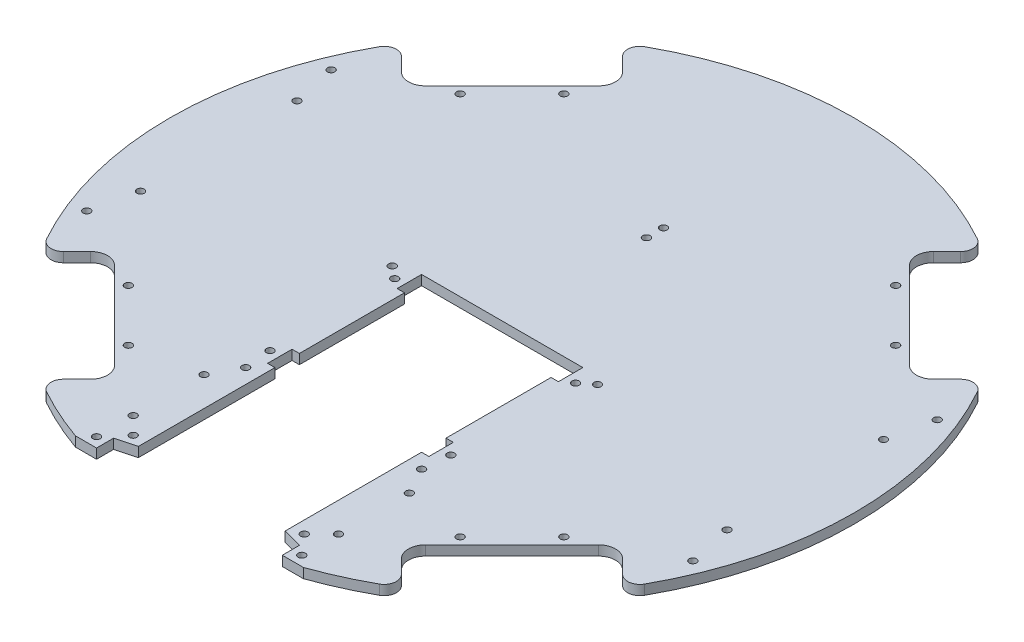
SolidWorks part; units mm, degrees
material "1060 Alloy"
ref_plane "Front Plane" through (0, 0, 0) normal (0, 0, 1) x (1, 0, 0)
ref_plane "Top Plane" through (0, 0, 0) normal (0, 1, 0) x (1, 0, 0)
ref_plane "Right Plane" through (0, 0, 0) normal (1, 0, 0) x (0, 0, -1)
sketch "Sketch1" plane through (0, 0, 0) normal (0, 1, 0) x (1, 0, 0)
  circle A0 centre (0, 0) radius 140
  dimension "D1" = 280
extrude "Boss-Extrude1" add sketch "Sketch1" along normal blind 4
sketch "Sketch7" plane through (0, 4, 0) normal (0, 1, 0) x (1, 0, 0)
  line L0 (-99.0303, -63.6043) -> (-63.6043, -99.0303)
  line L1 (-108.8591, -63.6043) -> (-121.6224, -76.3675)
  line L2 (-63.6043, -108.8591) -> (-76.3675, -121.6224)
  line L3 (-121.6224, -76.3675) -> (-76.3675, -121.6224)
  line L4 (0, 0) -> (-98.9949, -98.9949) construction
  line L7 (0, 0) -> (0, 130) construction
  circle A0 centre (0, 0) radius 140 construction
  arc A1 (-108.8591, -63.6043) -> (-99.0303, -63.6043) centre (-103.9447, -68.5186) cw
  arc A2 (-63.6043, -99.0303) -> (-63.6043, -108.8591) centre (-68.5186, -103.9447) cw
  dimension "D4" = 6.95
  dimension "D1" = 115
  dimension "D2" = 64
  dimension "D3" = 135
extrude "Cut-Extrude4" cut sketch "Sketch7" against normal up to next
sketch "Sketch9" plane through (0, 4, 0) normal (0, 1, 0) x (1, 0, 0)
  line L1 (-63.6043, -99.0303) -> (-99.0303, -63.6043) construction
  line L4 (-108.8591, -63.6043) -> (-119.0017, -73.7469) construction
  circle A0 centre (-89.0955, -67.8823) radius 1.5
  circle A1 centre (-67.8823, -89.0955) radius 1.5
  dimension "D4" = 3
  dimension "D1" = 4
  dimension "D2" = 30
  dimension "D3" = 17
  dimension "D5" = 4
extrude "Cut-Extrude6" cut sketch "Sketch9" against normal up to next
fillet "Fillet1" radius 5 2 edges at (-73.7469, 2, 119.0017) (-119.0017, 2, 73.7469)
pattern_circular "CirPattern1" count 4 over 360 about axis through (0, 0, 0) along (0, 1, 0) of "Cut-Extrude4", "Fillet1", "Cut-Extrude6"
sketch "Sketch2" plane through (0, 4, 0) normal (0, 1, 0) x (1, 0, 0)
  line L0 (-46.6476, -132) -> (-38, -132)
  line L1 (-30, -122.8564) -> (-30, -67)
  line L2 (-33, -4) -> (33, -4)
  line L3 (30, -67) -> (30, -122.8564)
  line L4 (38, -132) -> (46.6476, -132)
  line L5 (46.6476, -132) -> (46.6476, -140)
  line L6 (46.6476, -140) -> (-46.6476, -140)
  line L7 (-46.6476, -140) -> (-46.6476, -132)
  line L8 (-33, -57) -> (-33, -67)
  line L9 (-33, -67) -> (-30, -67)
  line L10 (33, -57) -> (33, -67)
  line L11 (33, -67) -> (30, -67)
  line L12 (-33, -57) -> (-30, -57)
  line L13 (-30, -57) -> (-30, -14)
  line L14 (-30, -14) -> (-33, -14)
  line L15 (-33, -14) -> (-33, -4)
  line L16 (33, -4) -> (33, -14)
  line L17 (33, -14) -> (30, -14)
  line L18 (30, -14) -> (30, -57)
  line L19 (30, -57) -> (33, -57)
  line L20 (-38, -132) -> (-38, -125)
  line L21 (-38, -125) -> (-30, -122.8564)
  line L22 (38, -132) -> (38, -125)
  line L23 (38, -125) -> (30, -122.8564)
  circle A0 centre (0, 0) radius 140 construction
  dimension "D8" = 3
  dimension "D5" = 63
  dimension "D6" = 66
  dimension "D1" = 8
  dimension "D2" = 65
  dimension "D3" = 60
  dimension "D4" = 16.6476
  dimension "D7" = 10
  dimension "D9" = 76
  dimension "D10" = 7
  dimension "D11" = 105
extrude "Cut-Extrude1" cut sketch "Sketch2" against normal up to next
fillet "Fillet3" radius 1.5 8 edges at (67.8823, 0, 90.5955) (89.0955, 0, 69.3823) (89.0955, 0, -66.3823) (67.8823, 0, -87.5955) (-67.8823, 0, -87.5955) (-89.0955, 0, -66.3823) (-67.8823, 0, 90.5955) (-89.0955, 0, 69.3823)
sketch "Sketch10" plane through (0, 4, 0) normal (0, 1, 0) x (1, 0, 0)
  line L0 (-33, -57) -> (-33, -67) construction
  line L1 (33, -67) -> (33, -57) construction
  line L2 (-33, -67) -> (-30, -67) construction
  line L4 (-30, -14) -> (-33, -14) construction
  line L5 (33, -4) -> (-33, -4) construction
  circle A0 centre (-37, -62) radius 1.5
  circle A1 centre (37, -62) radius 1.5
  circle A2 centre (-37, -11) radius 1.5
  circle A3 centre (37, -11) radius 1.5
  circle A4 centre (-42, -7) radius 1.5
  circle A5 centre (42, -7) radius 1.5
  point P17 (-31.5, -14)
  dimension "D3" = 3
  dimension "D1" = 4
  dimension "D2" = 4
  dimension "D4" = 5
  dimension "D5" = 3
  dimension "D6" = 3
  dimension "D7" = 5
  dimension "D8" = 5
extrude "Cut-Extrude7" cut sketch "Sketch10" against normal up to next
sketch "Sketch13" plane through (0, 4, 0) normal (0, 1, 0) x (1, 0, 0)
  line L0 (-38, -132) -> (-46.6476, -132) construction
  line L1 (-38, -132) -> (-46.6476, -132) construction
  circle A0 centre (-42, -84) radius 1.5
  circle A1 centre (-42, -113) radius 1.5
  circle A2 centre (42, -113) radius 1.5
  circle A3 centre (42, -84) radius 1.5
  dimension "D1" = 3
  dimension "D2" = 19
  dimension "D3" = 48
  dimension "D4" = 42
  dimension "D5" = 42
extrude "Cut-Extrude9" cut sketch "Sketch13" against normal up to next
sketch "Sketch16" plane through (0, 4, 0) normal (0, 1, 0) x (1, 0, 0)
  circle A0 centre (0, 62) radius 1.5
  circle A4 centre (0, 55) radius 1.5
  dimension "D2" = 3
  dimension "D5" = 3
  dimension "D1" = 62
  dimension "D7" = 55
extrude "Cut-Extrude12" cut sketch "Sketch16" against normal up to next
sketch "Sketch17" plane through (0, 4, 0) normal (0, 1, 0) x (1, 0, 0)
  circle A0 centre (-124, 50) radius 1.5
  circle A1 centre (-124, -50) radius 1.5
  circle A2 centre (124, 50) radius 1.5
  circle A3 centre (124, -50) radius 1.5
  dimension "D1" = 3
  dimension "D2" = 50
  dimension "D3" = 50
  dimension "D4" = 124
  dimension "D5" = 124
extrude "Cut-Extrude13" cut sketch "Sketch17" against normal up to next
sketch "Sketch18" plane through (0, 4, 0) normal (0, 1, 0) x (1, 0, 0)
  line L1 (-27, -4) -> (27, -4)
  line L2 (-27, -4) -> (-27, 46)
  line L3 (-27, 46) -> (27, 46)
  line L4 (27, -4) -> (27, 46)
  line L5 (33, -4) -> (-33, -4) construction
  dimension "D1" = 50
  dimension "D2" = 54
  dimension "D3" = 27
extrude "Cut-Extrude14" [suppressed] cut sketch "Sketch18" against normal blind 0.8
sketch "Sketch19" plane through (0, 4, 0) normal (0, 1, 0) x (1, 0, 0)
  line L0 (-38, -125) -> (-38, -132) construction
  line L1 (-38, -132) -> (-46.6476, -132) construction
  line L2 (38, -132) -> (38, -125) construction
  circle A0 centre (-42, -128) radius 1.5
  circle A1 centre (42, -128) radius 1.5
  dimension "D4" = 3
  dimension "D1" = 4
  dimension "D2" = 4
  dimension "D3" = 4
extrude "Cut-Extrude15" cut sketch "Sketch19" against normal up to next
sketch "Sketch20" [suppressed] plane through (0, 3, 0) normal (0, 1, 0) x (1, 0, 0)
  line L0 (27, 46) -> (-27, 46) construction
  line L1 (-6, 46) -> (6, 46)
  line L2 (-6, 46) -> (-6, 52)
  line L3 (-6, 52) -> (6, 52)
  line L4 (6, 46) -> (6, 52)
  circle A0 centre (0, 55) radius 1.5 construction
  dimension "D1" = 12
  dimension "D2" = 6
  dimension "D3" = 3
extrude "Cut-Extrude16" [suppressed] cut sketch "Sketch20" against normal up to surface (0.8 mm away)
fillet "Fillet4" [suppressed] radius 1.5
sketch "Sketch21" plane through (0, 4, 0) normal (0, 1, 0) x (1, 0, 0)
  circle A0 centre (-35, -120) radius 1.5
  circle A1 centre (-36, -73) radius 1.5
  circle A2 centre (35, -120) radius 1.5
  circle A3 centre (36, -73) radius 1.5
  circle A4 centre (-42, -128) radius 1.5 construction
  circle A5 centre (42, -128) radius 1.5 construction
  dimension "D1" = 7
  dimension "D3" = 3
  dimension "D2" = 8
  dimension "D4" = 47
  dimension "D5" = 1
  dimension "D6" = 1
  dimension "D7" = 7
extrude "Cut-Extrude17" cut sketch "Sketch21" against normal up to next
sketch "Sketch22" plane through (0, 4, 0) normal (0, 1, 0) x (1, 0, 0)
  circle A0 centre (120, 32) radius 1.5
  circle A1 centre (120, -32) radius 1.5
  circle A2 centre (-120, 32) radius 1.5
  circle A3 centre (-120, -32) radius 1.5
  dimension "D1" = 3
  dimension "D2" = 120
  dimension "D3" = 32
  dimension "D4" = 32
  dimension "D5" = 120
extrude "Cut-Extrude18" cut sketch "Sketch22" against normal up to next
